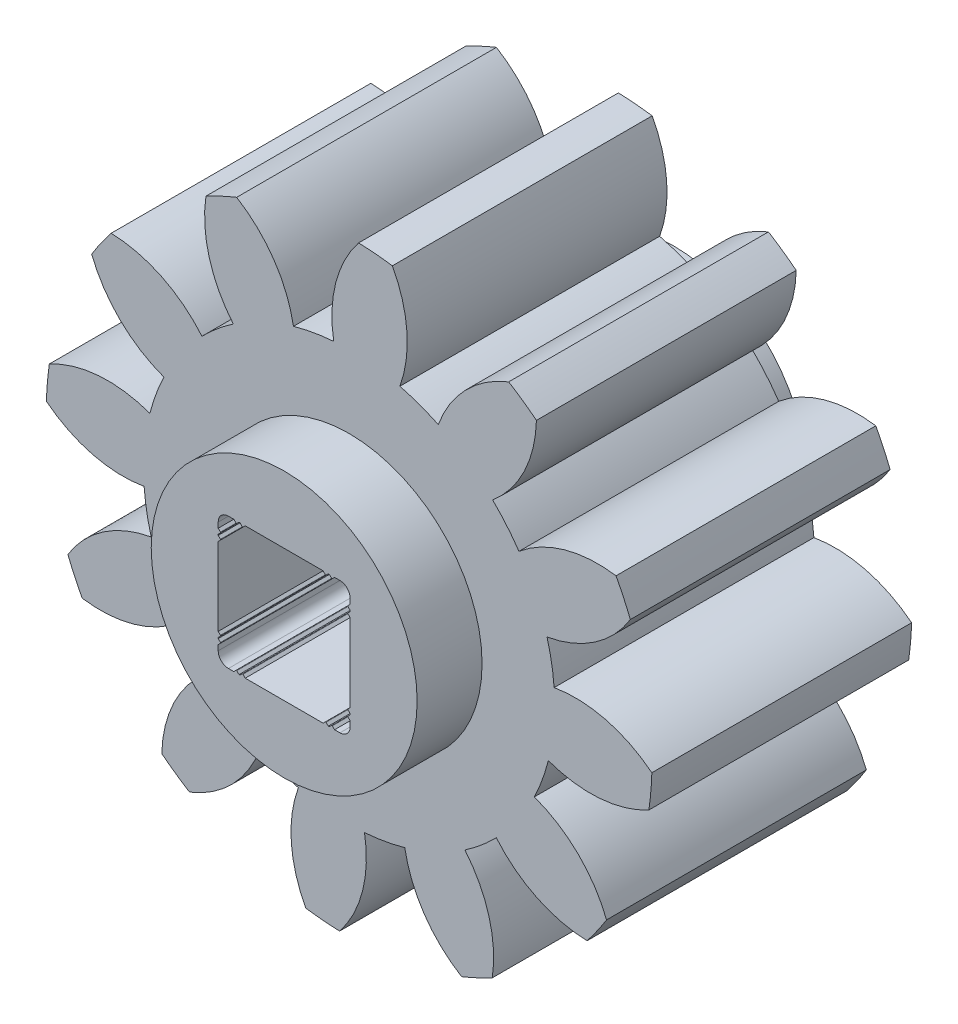
SolidWorks part; units mm, degrees
ref_plane "Front Plane" through (0, 0, 0) normal (0, 0, 1) x (1, 0, 0)
ref_plane "Top Plane" through (0, 0, 0) normal (0, 1, 0) x (1, 0, 0)
ref_plane "Right Plane" through (0, 0, 0) normal (1, 0, 0) x (0, 0, -1)
sketch "Sketch1" plane through (0, 0, 0) normal (0, 1, 0) x (1, 0, 0)
  line L0 (7.404, 3.175) -> (0, 3.175)
  line L1 (0, 3.175) -> (0, -3.175)
  line L2 (0, -3.175) -> (7.404, -3.175)
  line L3 (7.404, -3.175) -> (7.404, 3.175)
  line L4 (0, 3.175) -> (0, -3.175) construction
revolve "Revolve1" add sketch "Sketch1" angle 360 about L4
sketch "Sketch2" plane through (0, 0, -3.175) normal (0, 0, -1) x (-1, 0, 0)
  arc A0 (1.057, -7.3282) -> (3.9007, -6.2931) centre (0, 0) ccw
  arc A1 (3.9007, -6.2931) -> (2.1801, -4.528) centre (4.999, -3.5014) cw
  arc A2 (2.1801, -4.528) -> (1.2404, -4.87) centre (0, 0) cw
  arc A3 (1.2404, -4.87) -> (1.057, -7.3282) centre (-1.5788, -5.8955) cw
extrude "Cut-Extrude1" cut sketch "Sketch2" against normal through all
sketch "Sketch3" plane through (0, 0, -3.175) normal (0, 0, -1) x (-1, 0, 0)
  arc A0 (-2.7487, -6.8749) -> (0.2316, -7.4004) centre (0, 0) ccw
  arc A1 (0.2316, -7.4004) -> (-0.3759, -5.0114) centre (2.5786, -5.5318) cw
  arc A2 (-0.3759, -5.0114) -> (-1.3607, -4.8378) centre (0, 0) cw
  arc A3 (-1.3607, -4.8378) -> (-2.7487, -6.8749) centre (-4.3151, -4.3163) cw
extrude "Cut-Extrude2" cut sketch "Sketch3" against normal through all
sketch "Sketch4" plane through (0, 0, -3.175) normal (0, 0, -1) x (-1, 0, 0)
  arc A0 (-5.8179, -4.5795) -> (-3.4996, -6.5247) centre (0, 0) ccw
  arc A1 (-3.4996, -6.5247) -> (-2.8313, -4.152) centre (-0.5328, -6.08) cw
  arc A2 (-2.8313, -4.152) -> (-3.5973, -3.5093) centre (0, 0) cw
  arc A3 (-3.5973, -3.5093) -> (-5.8179, -4.5795) centre (-5.8951, -1.5805) cw
extrude "Cut-Extrude3" cut sketch "Sketch4" against normal through all
sketch "Sketch5" plane through (0, 0, -3.175) normal (0, 0, -1) x (-1, 0, 0)
  arc A0 (-7.3282, -1.057) -> (-6.2931, -3.9007) centre (0, 0) ccw
  arc A1 (-6.2931, -3.9007) -> (-4.528, -2.1801) centre (-3.5014, -4.999) cw
  arc A2 (-4.528, -2.1801) -> (-4.87, -1.2404) centre (0, 0) cw
  arc A3 (-4.87, -1.2404) -> (-7.3282, -1.057) centre (-5.8955, 1.5788) cw
extrude "Cut-Extrude4" cut sketch "Sketch5" against normal through all
sketch "Sketch6" plane through (0, 0, -3.175) normal (0, 0, -1) x (-1, 0, 0)
  arc A0 (-6.8749, 2.7487) -> (-7.4004, -0.2316) centre (0, 0) ccw
  arc A1 (-7.4004, -0.2316) -> (-5.0114, 0.3759) centre (-5.5318, -2.5786) cw
  arc A2 (-5.0114, 0.3759) -> (-4.8378, 1.3607) centre (0, 0) cw
  arc A3 (-4.8378, 1.3607) -> (-6.8749, 2.7487) centre (-4.3163, 4.3151) cw
extrude "Cut-Extrude5" cut sketch "Sketch6" against normal through all
sketch "Sketch7" plane through (0, 0, -3.175) normal (0, 0, -1) x (-1, 0, 0)
  arc A0 (-4.5795, 5.8179) -> (-6.5247, 3.4996) centre (0, 0) ccw
  arc A1 (-6.5247, 3.4996) -> (-4.152, 2.8313) centre (-6.08, 0.5328) cw
  arc A2 (-4.152, 2.8313) -> (-3.5093, 3.5973) centre (0, 0) cw
  arc A3 (-3.5093, 3.5973) -> (-4.5795, 5.8179) centre (-1.5805, 5.8951) cw
extrude "Cut-Extrude6" cut sketch "Sketch7" against normal through all
sketch "Sketch8" plane through (0, 0, -3.175) normal (0, 0, -1) x (-1, 0, 0)
  arc A0 (-1.057, 7.3282) -> (-3.9007, 6.2931) centre (0, 0) ccw
  arc A1 (-3.9007, 6.2931) -> (-2.1801, 4.528) centre (-4.999, 3.5014) cw
  arc A2 (-2.1801, 4.528) -> (-1.2404, 4.87) centre (0, 0) cw
  arc A3 (-1.2404, 4.87) -> (-1.057, 7.3282) centre (1.5788, 5.8955) cw
extrude "Cut-Extrude7" cut sketch "Sketch8" against normal through all
sketch "Sketch9" plane through (0, 0, -3.175) normal (0, 0, -1) x (-1, 0, 0)
  arc A0 (2.7487, 6.8749) -> (-0.2316, 7.4004) centre (0, 0) ccw
  arc A1 (-0.2316, 7.4004) -> (0.3759, 5.0114) centre (-2.5786, 5.5318) cw
  arc A2 (0.3759, 5.0114) -> (1.3607, 4.8378) centre (0, 0) cw
  arc A3 (1.3607, 4.8378) -> (2.7487, 6.8749) centre (4.3151, 4.3163) cw
extrude "Cut-Extrude8" cut sketch "Sketch9" against normal through all
sketch "Sketch10" plane through (0, 0, -3.175) normal (0, 0, -1) x (-1, 0, 0)
  arc A0 (5.8179, 4.5795) -> (3.4996, 6.5247) centre (0, 0) ccw
  arc A1 (3.4996, 6.5247) -> (2.8313, 4.152) centre (0.5328, 6.08) cw
  arc A2 (2.8313, 4.152) -> (3.5973, 3.5093) centre (0, 0) cw
  arc A3 (3.5973, 3.5093) -> (5.8179, 4.5795) centre (5.8951, 1.5805) cw
extrude "Cut-Extrude9" cut sketch "Sketch10" against normal through all
sketch "Sketch11" plane through (0, 0, -3.175) normal (0, 0, -1) x (-1, 0, 0)
  arc A0 (7.3282, 1.057) -> (6.2931, 3.9007) centre (0, 0) ccw
  arc A1 (6.2931, 3.9007) -> (4.528, 2.1801) centre (3.5014, 4.999) cw
  arc A2 (4.528, 2.1801) -> (4.87, 1.2404) centre (0, 0) cw
  arc A3 (4.87, 1.2404) -> (7.3282, 1.057) centre (5.8955, -1.5788) cw
extrude "Cut-Extrude10" cut sketch "Sketch11" against normal through all
sketch "Sketch12" plane through (0, 0, -3.175) normal (0, 0, -1) x (-1, 0, 0)
  arc A0 (6.8749, -2.7487) -> (7.4004, 0.2316) centre (0, 0) ccw
  arc A1 (7.4004, 0.2316) -> (5.0114, -0.3759) centre (5.5318, 2.5786) cw
  arc A2 (5.0114, -0.3759) -> (4.8378, -1.3607) centre (0, 0) cw
  arc A3 (4.8378, -1.3607) -> (6.8749, -2.7487) centre (4.3163, -4.3151) cw
extrude "Cut-Extrude11" cut sketch "Sketch12" against normal through all
sketch "Sketch13" plane through (0, 0, -3.175) normal (0, 0, -1) x (-1, 0, 0)
  arc A0 (4.5795, -5.8179) -> (6.5247, -3.4996) centre (0, 0) ccw
  arc A1 (6.5247, -3.4996) -> (4.152, -2.8313) centre (6.08, -0.5328) cw
  arc A2 (4.152, -2.8313) -> (3.5093, -3.5973) centre (0, 0) cw
  arc A3 (3.5093, -3.5973) -> (4.5795, -5.8179) centre (1.5805, -5.8951) cw
extrude "Cut-Extrude12" cut sketch "Sketch13" against normal through all
sketch "Sketch14" plane through (0, 0, 3.175) normal (0, 0, 1) x (1, 0, 0)
  circle A0 centre (0, 0) radius 3.25
extrude "Boss-Extrude1" add sketch "Sketch14" along normal blind 1.5875
sketch "Sketch15" plane through (0, 0, -3.175) normal (0, 0, -1) x (-1, 0, 0)
  circle A0 centre (0, 0) radius 3.25
extrude "Boss-Extrude2" add sketch "Sketch15" along normal blind 1.5875
sketch "Sketch16" plane through (0, 0, -4.7625) normal (0, 0, -1) x (-1, 0, 0)
  line L0 (1.4855, 1.2315) -> (1.6125, 1.2315)
  line L1 (1.6125, 1.2315) -> (1.6125, 1.6125)
  line L2 (1.6125, 1.6125) -> (1.2315, 1.6125)
  line L3 (1.2315, 1.6125) -> (1.2315, 1.4855)
  line L4 (1.2315, 1.4855) -> (1.0918, 1.6252)
  line L5 (1.0918, 1.6252) -> (0.9521, 1.4855)
  line L6 (0.9521, 1.4855) -> (0.9521, 1.6125)
  line L7 (0.9521, 1.6125) -> (-0.9521, 1.6125)
  line L8 (-0.9521, 1.6125) -> (-0.9521, 1.4851)
  line L9 (-0.9521, 1.4851) -> (-1.0918, 1.6252)
  line L10 (-1.0918, 1.6252) -> (-1.2315, 1.4851)
  line L11 (-1.2315, 1.4851) -> (-1.2315, 1.6125)
  line L12 (-1.2315, 1.6125) -> (-1.6125, 1.6125)
  line L13 (-1.6125, 1.6125) -> (-1.6125, 1.2315)
  line L14 (-1.6125, 1.2315) -> (-1.4851, 1.2315)
  line L15 (-1.4851, 1.2315) -> (-1.6252, 1.0918)
  line L16 (-1.6252, 1.0918) -> (-1.4851, 0.9521)
  line L17 (-1.4851, 0.9521) -> (-1.6125, 0.9521)
  line L18 (-1.6125, 0.9521) -> (-1.6125, -0.9521)
  line L19 (-1.6125, -0.9521) -> (-1.4855, -0.9521)
  line L20 (-1.4855, -0.9521) -> (-1.6252, -1.0918)
  line L21 (-1.6252, -1.0918) -> (-1.4855, -1.2315)
  line L22 (-1.4855, -1.2315) -> (-1.6125, -1.2315)
  line L23 (-1.6125, -1.2315) -> (-1.6125, -1.6125)
  line L24 (-1.6125, -1.6125) -> (-1.2315, -1.6125)
  line L25 (-1.2315, -1.6125) -> (-1.2315, -1.4855)
  line L26 (-1.2315, -1.4855) -> (-1.0918, -1.6252)
  line L27 (-1.0918, -1.6252) -> (-0.9521, -1.4855)
  line L28 (-0.9521, -1.4855) -> (-0.9521, -1.6125)
  line L29 (-0.9521, -1.6125) -> (0.9521, -1.6125)
  line L30 (0.9521, -1.6125) -> (0.9521, -1.4851)
  line L31 (0.9521, -1.4851) -> (1.0918, -1.6252)
  line L32 (1.0918, -1.6252) -> (1.2315, -1.4851)
  line L33 (1.2315, -1.4851) -> (1.2315, -1.6125)
  line L34 (1.2315, -1.6125) -> (1.6125, -1.6125)
  line L35 (1.6125, -1.6125) -> (1.6125, -1.2315)
  line L36 (1.6125, -1.2315) -> (1.4851, -1.2315)
  line L37 (1.4851, -1.2315) -> (1.6252, -1.0918)
  line L38 (1.6252, -1.0918) -> (1.4851, -0.9521)
  line L39 (1.4851, -0.9521) -> (1.6125, -0.9521)
  line L40 (1.6125, -0.9521) -> (1.6125, 0.9521)
  line L41 (1.6125, 0.9521) -> (1.4855, 0.9521)
  line L42 (1.4855, 0.9521) -> (1.6252, 1.0918)
  line L43 (1.6252, 1.0918) -> (1.4855, 1.2315)
extrude "Cut-Extrude13" cut sketch "Sketch16" against normal through all
draft "Draft1" type of draft neutral plane draft angle 44.905 faces to draft 1 face at (-1.5488, -0.9521, 0) neutral plane through (-1.6125, -0.9521, 4.7625) neutral plane normal (1, 0, 0) parameters "D1"=44.905
draft "Draft2" type of draft neutral plane draft angle 45 faces to draft 1 face at (-1.549, 0.9521, 0) neutral plane through (-1.6125, -0.9521, 4.7625) neutral plane normal (1, 0, 0) parameters "D1"=45
draft "Draft3" type of draft neutral plane draft angle 45 faces to draft 1 face at (0.9521, -1.549, 0) neutral plane through (0.9521, -1.6125, 4.7625) neutral plane normal (0, 1, 0) parameters "D1"=45
draft "Draft4" type of draft neutral plane draft angle 44.905 faces to draft 1 face at (-0.9521, -1.5488, 0) neutral plane through (0.9521, -1.6125, 4.7625) neutral plane normal (0, 1, 0) parameters "D1"=44.905
draft "Draft5" type of draft neutral plane draft angle 44.905 faces to draft 1 face at (1.5488, 0.9521, 0) neutral plane through (1.6125, 0.9521, 4.7625) neutral plane normal (-1, 0, 0) parameters "D1"=44.905
draft "Draft6" type of draft neutral plane draft angle 45 faces to draft 1 face at (1.549, -0.9521, 0) neutral plane through (1.6125, 0.9521, 4.7625) neutral plane normal (-1, 0, 0) parameters "D1"=45
draft "Draft7" type of draft neutral plane draft angle 45 faces to draft 1 face at (-0.9521, 1.549, 0) neutral plane through (-0.9521, 1.6125, 4.7625) neutral plane normal (0, -1, 0) parameters "D1"=45
draft "Draft8" type of draft neutral plane draft angle 44.905 faces to draft 1 face at (0.9521, 1.5488, 0) neutral plane through (-0.9521, 1.6125, 4.7625) neutral plane normal (0, -1, 0) parameters "D1"=44.905
draft "Draft9" type of draft neutral plane draft angle 45 faces to draft 1 face at (1.2315, -1.549, 0) neutral plane through (1.6125, -1.6125, 4.7625) neutral plane normal (0, 1, 0) parameters "D1"=45
draft "Draft10" type of draft neutral plane draft angle 44.81 faces to draft 1 face at (1.549, -1.2315, 0) neutral plane through (1.6125, -1.2315, 4.7625) neutral plane normal (-1, 0, 0) parameters "D1"=44.81
draft "Draft11" type of draft neutral plane draft angle 44.905 faces to draft 1 face at (1.5488, 1.2315, 0) neutral plane through (1.6125, 1.6125, 4.7625) neutral plane normal (-1, 0, 0) parameters "D1"=44.905
draft "Draft12" type of draft neutral plane draft angle 44.905 faces to draft 1 face at (1.2315, 1.5488, 0) neutral plane through (1.2315, 1.6125, 4.7625) neutral plane normal (0, -1, 0) parameters "D1"=44.905
draft "Draft13" type of draft neutral plane draft angle 44.905 faces to draft 1 face at (-1.2315, -1.5488, 0) neutral plane through (-1.2315, -1.6125, 4.7625) neutral plane normal (0, 1, 0) parameters "D1"=44.905
draft "Draft14" type of draft neutral plane draft angle 44.905 faces to draft 1 face at (-1.5488, -1.2315, 0) neutral plane through (-1.6125, -1.6125, 4.7625) neutral plane normal (1, 0, 0) parameters "D1"=44.905
draft "Draft15" type of draft neutral plane draft angle 45 faces to draft 1 face at (-1.2315, 1.549, 0) neutral plane through (-1.6125, 1.6125, 4.7625) neutral plane normal (0, -1, 0) parameters "D1"=45
draft "Draft16" type of draft neutral plane draft angle 44.81 faces to draft 1 face at (-1.549, 1.2315, 0) neutral plane through (-1.6125, 1.2315, 4.7625) neutral plane normal (1, 0, 0) parameters "D1"=44.81
fillet "Fillet1" radius 0.0127 16 edges at (1.168, -1.549, 0) (-1.168, 1.549, 0) (1.5488, 1.0156, 0) (1.5488, 1.168, 0) (-1.0156, 1.549, 0) (1.168, 1.5488, 0) (1.5488, -1.1682, 0) (-1.168, -1.5488, 0) (1.0156, 1.5488, 0) (-1.0156, -1.5488, 0) (1.549, -1.0156, 0) (1.0156, -1.549, 0) (-1.5488, -1.0156, 0) (-1.549, 1.0156, 0) (-1.5488, 1.1682, 0) (-1.5488, -1.168, 0)
chamfer "Chamfer1" distance 0.018 angle 45 4 edges at (1.0918, -1.6252, 0) (-1.0918, 1.6252, 0) (1.6252, -1.0918, 0) (-1.6252, 1.0918, 0)
chamfer "Chamfer2" distance 0.018 angle 45.095 4 edges at (1.6252, 1.0918, 0) (-1.0918, -1.6252, 0) (-1.6252, -1.0918, 0) (1.0918, 1.6252, 0)
fillet "Fillet2" radius 0.25 4 edges at (-1.6125, -1.6125, 0) (1.6125, 1.6125, 0) (-1.6125, 1.6125, 0) (1.6125, -1.6125, 0)
